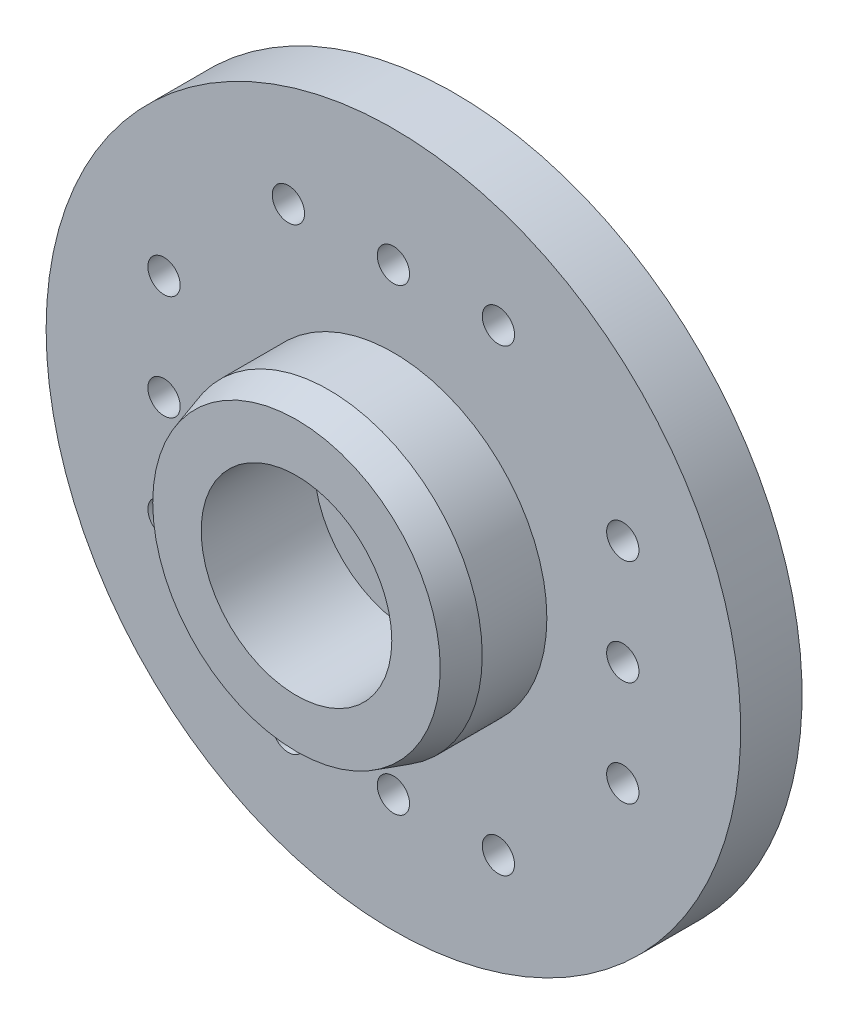
SolidWorks part; units mm, degrees
ref_plane "Front Plane" through (0, 0, 0) normal (0, 0, 1) x (1, 0, 0)
ref_plane "Top Plane" through (0, 0, 0) normal (0, 1, 0) x (1, 0, 0)
ref_plane "Right Plane" through (0, 0, 0) normal (1, 0, 0) x (0, 0, -1)
sketch "Sketch1" plane through (0, 0, 0) normal (0, 0, 1) x (1, 0, 0)
  line L0 (-3.25, 7.1) -> (3.25, 7.1) construction
  circle A0 centre (0, 0) radius 10.75
  circle A1 centre (-3.25, 7.1) radius 0.5
  circle A2 centre (0, 7.1) radius 0.5
  circle A3 centre (3.25, 7.1) radius 0.5
  circle A4 centre (7.1, 3.25) radius 0.5
  circle A5 centre (7.1, 0) radius 0.5
  circle A6 centre (7.1, -3.25) radius 0.5
  circle A7 centre (3.25, -7.1) radius 0.5
  circle A8 centre (0, -7.1) radius 0.5
  circle A9 centre (-3.25, -7.1) radius 0.5
  circle A10 centre (-7.1, -3.25) radius 0.5
  circle A11 centre (-7.1, 0) radius 0.5
  circle A12 centre (-7.1, 3.25) radius 0.5
  point P9 (0, 7.1)
  point P31 (0, 0)
  dimension "D1" = 21.5
  dimension "D4" = 1
  dimension "D2" = 6.5
  dimension "D3" = 7.1
  dimension "D5" = 4
extrude "Boss-Extrude1" add sketch "Sketch1" along normal blind 1.9
sketch "Sketch2" plane through (0, 0, 1.9) normal (0, 0, 1) x (1, 0, 0)
  circle A0 centre (0, 0) radius 4.75
  dimension "D1" = 9.5
extrude "Boss-Extrude2" add sketch "Sketch2" along normal blind 3
ref_plane "Plane1" through (0, 0, 3.9) normal (0, 0, 1) x (1, 0, 0)
sketch "Sketch5" plane through (0, 0, 0) normal (0, 1, 0) x (1, 0, 0)
  line L0 (4.75, -3.9) -> (4.45, -4.9)
  line L1 (-11.825, -3.9) -> (11.825, -3.9) construction
  line L2 (4.75, -4.9) -> (4.75, -1.9) construction
  line L3 (-4.75, -4.9) -> (4.75, -4.9) construction
  line L4 (-4.45, -4.9) -> (-4.75, -3.9) construction
  line L5 (-4.45, -4.9) -> (4.45, -4.9) construction
  line L6 (4.45, -4.9) -> (4.75, -4.9)
  line L7 (4.75, -4.9) -> (4.75, -3.9)
  line L8 (0, -6.0984) -> (0, 1.24) construction
  point P10 (0, -4.9)
  dimension "D1" = 8.9
revolve "Cut-Revolve1" cut sketch "Sketch5" angle 360 about L8
sketch "Sketch7" plane through (0, 0, 4.9) normal (0, 0, 1) x (1, 0, 0)
  circle A0 centre (0, 0) radius 2.95
  dimension "D1" = 5.9
extrude "Cut-Extrude1" cut sketch "Sketch7" against normal blind 3.5
sketch "Sketch8" plane through (0, 0, 0) normal (0, 0, -1) x (-1, 0, 0)
  circle A0 centre (0, 0) radius 3.25
  circle A1 centre (0, 0) radius 2.75
  dimension "D1" = 6.5
  dimension "D2" = 0.5
extrude "Boss-Extrude3" add sketch "Sketch8" along normal blind 1
sketch "Sketch9" plane through (0, 0, 0) normal (0, 0, -1) x (-1, 0, 0)
  circle A0 centre (0, 0) radius 3.25
  circle A1 centre (0, 0) radius 4.25
  dimension "D1" = 8.5
extrude "Cut-Extrude2" cut sketch "Sketch9" against normal blind 0.4
sketch "Sketch10" plane through (0, 0, 0) normal (0, 0, -1) x (-1, 0, 0)
  circle A0 centre (0, 0) radius 1.45
  dimension "D1" = 2.9
extrude "Cut-Extrude3" cut sketch "Sketch10" against normal through all
